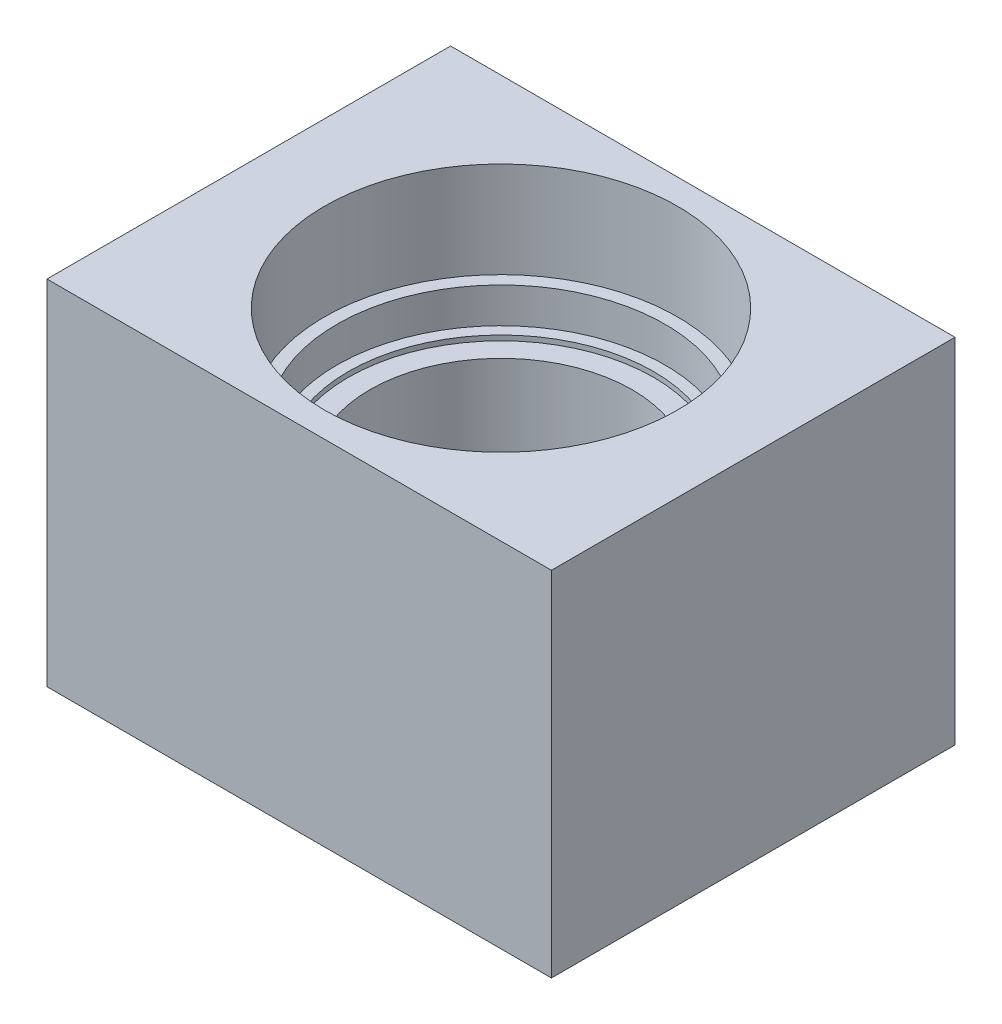
SolidWorks part; units mm, degrees
ref_plane "Front Plane" through (0, 0, 0) normal (0, 0, 1) x (1, 0, 0)
ref_plane "Top Plane" through (0, 0, 0) normal (0, 1, 0) x (1, 0, 0)
ref_plane "Right Plane" through (0, 0, 0) normal (1, 0, 0) x (0, 0, -1)
sketch "Sketch1" plane through (0, 0, 0) normal (0, 1, 0) x (1, 0, 0)
  line L1 (-50, 40) -> (50, 40)
  line L2 (-50, 40) -> (-50, -40)
  line L3 (-50, -40) -> (50, -40)
  line L4 (50, 40) -> (50, -40)
  line L5 (-50, 40) -> (50, -40) construction
  line L6 (-50, -40) -> (50, 40) construction
  circle A1 centre (0, 0) radius 26
  point P0 (0, 0)
  dimension "D3" = 52
  dimension "D1" = 80
  dimension "D2" = 100
extrude "Boss-Extrude1" add sketch "Sketch1" along normal blind 70
sketch "Sketch2" plane through (0, 70, 0) normal (0, 1, 0) x (1, 0, 0)
  circle A0 centre (0, 0) radius 32.5
  dimension "D1" = 65
extrude "Cut-Extrude1" cut sketch "Sketch2" against normal blind 27
sketch "Sketch4" plane through (0, 43, 0) normal (0, 1, 0) x (1, 0, 0)
  circle A0 centre (0, 0) radius 30.25
  circle M3 centre (0, 0) radius 32.5
  dimension "D1" = 60.5
extrude "Boss-Extrude2" add sketch "Sketch4" along normal blind 1 contours A0 M3
sketch "Sketch5" plane through (0, 70, 0) normal (0, 1, 0) x (1, 0, 0)
  circle A0 centre (0, 0) radius 35
  dimension "D1" = 70
extrude "Cut-Extrude2" cut sketch "Sketch5" against normal offset from surface (19 mm away) 7 up to face at (0, 44, 30.25)
sketch "Sketch6" plane through (0, 0, 0) normal (0, -1, 0) x (1, 0, 0)
  circle A0 centre (0, 0) radius 32.5
  dimension "D1" = 65
extrude "Cut-Extrude3" cut sketch "Sketch6" against normal blind 7
